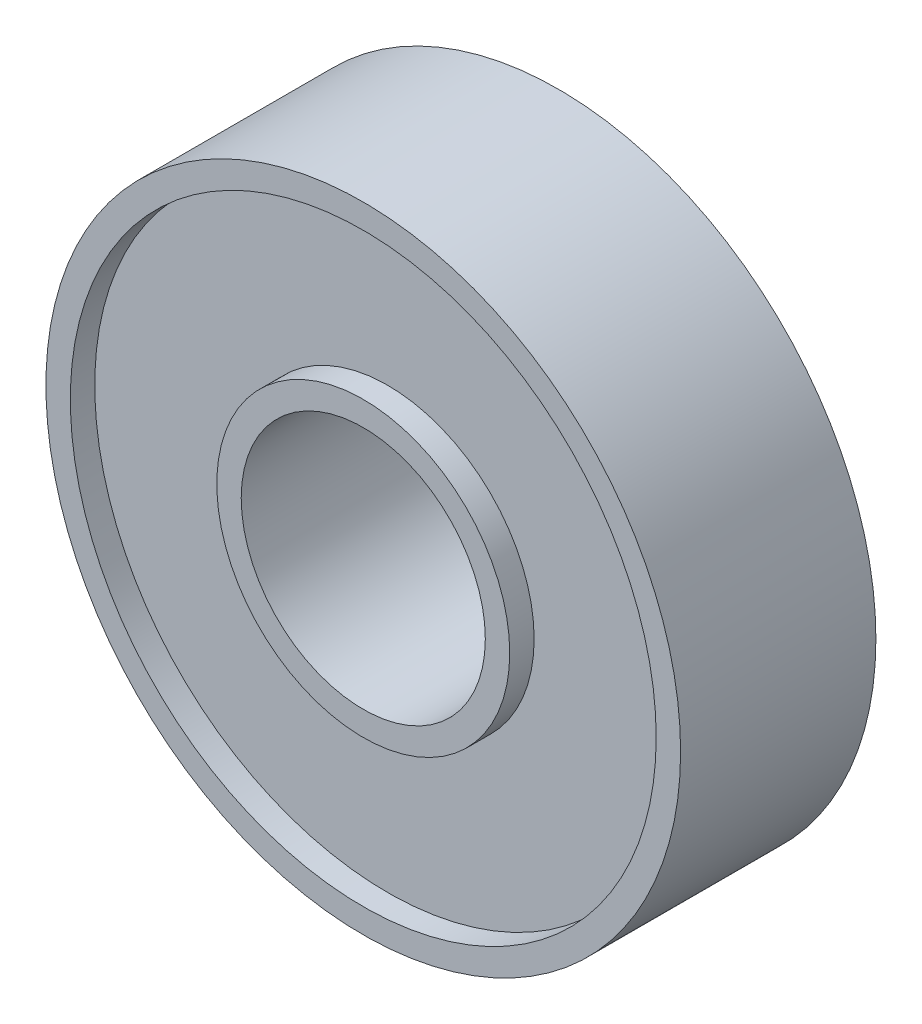
SolidWorks part; units mm, degrees
ref_plane "前视基准面" through (0, 0, 0) normal (0, 0, 1) x (1, 0, 0)
ref_plane "上视基准面" through (0, 0, 0) normal (0, 1, 0) x (1, 0, 0)
ref_plane "右视基准面" through (0, 0, 0) normal (1, 0, 0) x (0, 0, -1)
sketch "草图1" plane through (0, 0, 0) normal (0, 0, 1) x (1, 0, 0)
  circle A0 centre (0, 0) radius 6.5
  circle A3 centre (0, 0) radius 2.5
extrude "凸台-拉伸1" add sketch "草图1" along normal blind 4
sketch "草图2" plane through (0, 0, 4) normal (0, 0, 1) x (1, 0, 0)
  circle A0 centre (0, 0) radius 6
  circle A1 centre (0, 0) radius 3
extrude "切除-拉伸1" cut sketch "草图2" against normal blind 0.5
sketch "草图3" plane through (0, 0, 0) normal (0, 0, -1) x (-1, 0, 0)
  circle A0 centre (0, 0) radius 6
  circle A1 centre (0, 0) radius 3
extrude "切除-拉伸2" cut sketch "草图3" against normal blind 0.5
